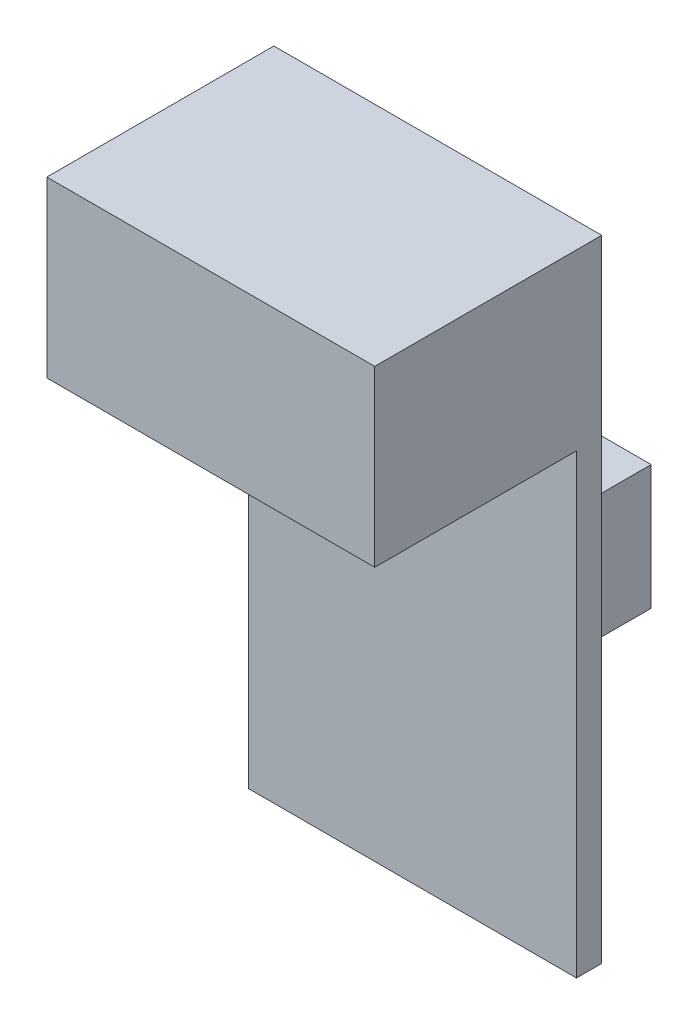
SolidWorks part; units mm, degrees
ref_plane "前视基准面" through (0, 0, 0) normal (0, 0, 1) x (1, 0, 0)
ref_plane "上视基准面" through (0, 0, 0) normal (0, 1, 0) x (1, 0, 0)
ref_plane "右视基准面" through (0, 0, 0) normal (1, 0, 0) x (0, 0, -1)
sketch "草图1" plane through (0, 0, 0) normal (0, 0, 1) x (1, 0, 0)
  line L1 (6.5, -12.5) -> (-6.5, -12.5)
  line L2 (6.5, -12.5) -> (6.5, 12.5)
  line L3 (6.5, 12.5) -> (-6.5, 12.5)
  line L4 (-6.5, -12.5) -> (-6.5, 12.5)
  line L5 (6.5, -12.5) -> (-6.5, 12.5) construction
  line L6 (6.5, 12.5) -> (-6.5, -12.5) construction
  point P0 (0, 0)
  dimension "D1" = 13
  dimension "D2" = 25
extrude "凸台-拉伸1" add sketch "草图1" along normal blind 1
sketch "草图2" plane through (0, 0, 1) normal (0, 0, 1) x (1, 0, 0)
  line L0 (6.5, -12.5) -> (6.5, 12.5) construction
  line L1 (-6.5, 12.5) -> (6.5, 12.5)
  line L2 (-6.5, 12.5) -> (-6.5, 5.6014)
  line L3 (-6.5, 5.6014) -> (6.5, 5.6014)
  line L4 (6.5, 12.5) -> (6.5, 5.6014)
extrude "凸台-拉伸2" add sketch "草图2" along normal blind 8
sketch "草图3" plane through (0, 0, 0) normal (0, 0, -1) x (-1, 0, 0)
  circle A0 centre (-4.8664, 8.6842) radius 0.5273
  circle A1 centre (-1.8664, 8.6842) radius 0.5273
  circle A2 centre (1.1336, 8.6842) radius 0.5273
  circle A3 centre (4.1336, 8.6842) radius 0.5273
  circle A4 centre (-1.8664, 6.6842) radius 0.5273
  circle A5 centre (1.1336, 6.6842) radius 0.5273
  circle A6 centre (4.1336, 6.6842) radius 0.5273
  circle A7 centre (-4.8664, 6.6842) radius 0.5273
  dimension "D1" = 4
  dimension "D2" = 2
extrude "凸台-拉伸3" add sketch "草图3" along normal blind 1
fillet "圆角3" radius 0.5 1 edges at (4.3391, 8.6842, -1)
fillet "圆角4" radius 0.5 7 edges at (4.3391, 6.6842, -1) (1.3391, 6.6842, -1) (-1.6609, 6.6842, -1) (-4.6609, 6.6842, -1) (-4.6609, 8.6842, -1) (-1.6609, 8.6842, -1) (1.3391, 8.6842, -1)
sketch "草图4" plane through (0, 0, 0) normal (0, 0, -1) x (-1, 0, 0)
  line L1 (-5.4599, 2.6086) -> (0.2427, 2.6086)
  line L2 (-5.4599, 2.6086) -> (-5.4599, -2.3255)
  line L3 (-5.4599, -2.3255) -> (0.2427, -2.3255)
  line L4 (0.2427, 2.6086) -> (0.2427, -2.3255)
extrude "凸台-拉伸4" add sketch "草图4" along normal blind 3
sketch "草图5" plane through (0, 0, 0) normal (0, 0, -1) x (-1, 0, 0)
  line L1 (1.6986, 3.1748) -> (5.9856, 3.1748)
  line L2 (1.6986, 3.1748) -> (1.6986, -2.8108)
  line L3 (1.6986, -2.8108) -> (5.9856, -2.8108)
  line L4 (5.9856, 3.1748) -> (5.9856, -2.8108)
extrude "凸台-拉伸5" add sketch "草图5" along normal blind 1.5
sketch "草图6" plane through (0, 0, 0) normal (0, 0, -1) x (-1, 0, 0)
  line L1 (3.0737, -4.0241) -> (3.5995, -4.0241)
  line L2 (3.0737, -4.0241) -> (3.0737, -4.3477)
  line L3 (3.0737, -4.3477) -> (3.5995, -4.3477)
  line L4 (3.5995, -4.0241) -> (3.5995, -4.3477)
  line L5 (4.5701, -5.2779) -> (4.7723, -5.2779)
  line L6 (4.5701, -5.2779) -> (4.5701, -5.7228)
  line L7 (4.5701, -5.7228) -> (4.7723, -5.7228)
  line L8 (4.7723, -5.2779) -> (4.7723, -5.7228)
  line L9 (5.0554, -4.1859) -> (5.4599, -4.1859)
  line L10 (5.0554, -4.1859) -> (5.0554, -4.3477)
  line L11 (5.0554, -4.3477) -> (5.4599, -4.3477)
  line L12 (5.4599, -4.1859) -> (5.4599, -4.3477)
  line L13 (1.2133, -5.2779) -> (2.3457, -5.2779)
  line L14 (1.2133, -5.2779) -> (1.2133, -5.7228)
  line L15 (1.2133, -5.7228) -> (2.3457, -5.7228)
  line L16 (2.3457, -5.2779) -> (2.3457, -5.7228)
  line L17 (-4.0848, -4.6308) -> (-3.6803, -4.6308)
  line L18 (-4.0848, -4.6308) -> (-4.0848, -5.2779)
  line L19 (-4.0848, -5.2779) -> (-3.6803, -5.2779)
  line L20 (-3.6803, -4.6308) -> (-3.6803, -5.2779)
  line L21 (-1.9413, -3.4175) -> (-1.6986, -3.4175)
  line L22 (-1.9413, -3.4175) -> (-1.9413, -4.0241)
  line L23 (-1.9413, -4.0241) -> (-1.6986, -4.0241)
  line L24 (-1.6986, -3.4175) -> (-1.6986, -4.0241)
extrude "凸台-拉伸6" add sketch "草图6" along normal blind 0.5
